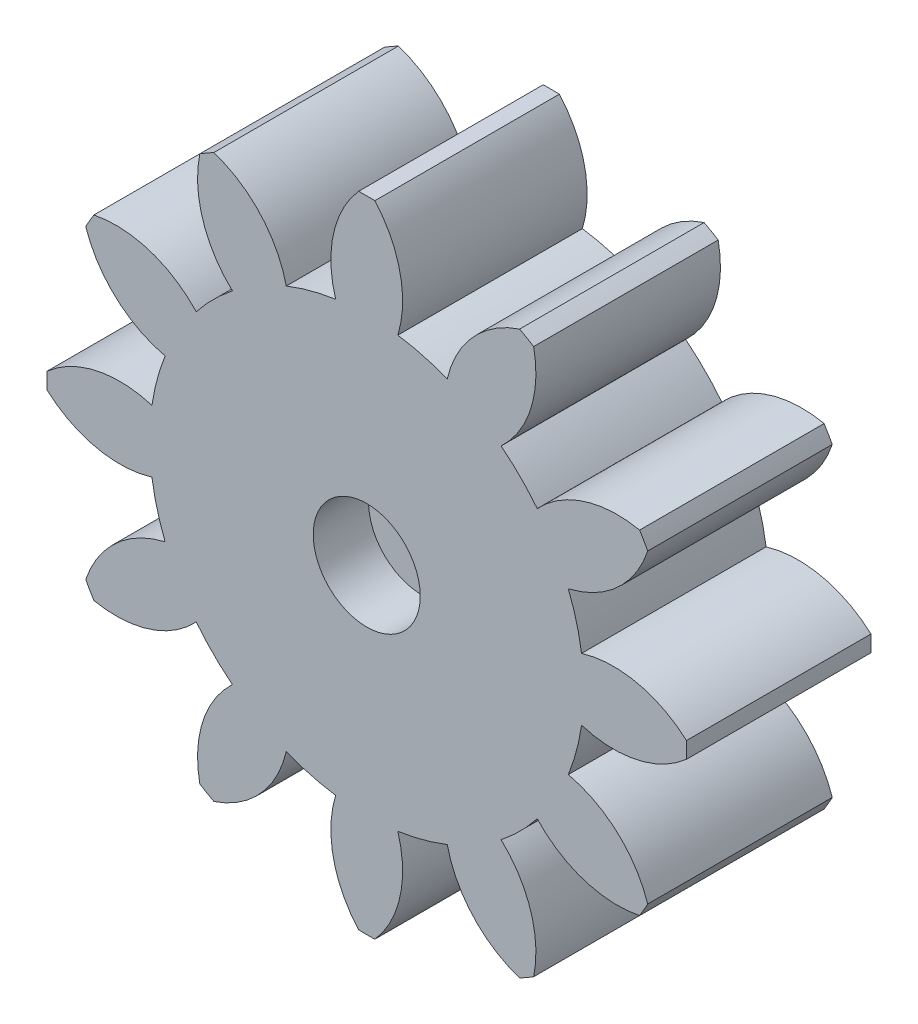
SolidWorks part; units mm, degrees
ref_plane "Front Plane" through (0, 0, 0) normal (0, 0, 1) x (1, 0, 0)
ref_plane "Top Plane" through (0, 0, 0) normal (0, 1, 0) x (1, 0, 0)
ref_plane "Right Plane" through (0, 0, 0) normal (1, 0, 0) x (0, 0, -1)
sketch "Sketch1" plane through (0, 0, 0) normal (0, 0, 1) x (1, 0, 0)
  arc A96 (10.9244, -4.3614) -> (11.6416, -1.6851) centre (0, 0) ccw
  arc A97 (11.6416, -1.6851) -> (17.3299, -0.4402) centre (13.3779, 3.9992) ccw
  arc A98 (17.3299, -0.4402) -> (17.3299, 0.4402) centre (0, 0) ccw
  arc A99 (17.3299, 0.4402) -> (11.6416, 1.6851) centre (13.3779, -3.9992) ccw
  arc A100 (11.6416, 1.6851) -> (10.9244, 4.3614) centre (0, 0) ccw
  arc A101 (10.9244, 4.3614) -> (15.2282, 8.2838) centre (9.586, 10.1524) ccw
  arc A102 (15.2282, 8.2838) -> (14.7881, 9.0462) centre (0, 0) ccw
  arc A103 (14.7881, 9.0462) -> (9.2393, 7.2801) centre (13.5852, 3.2255) ccw
  arc A104 (9.2393, 7.2801) -> (7.2801, 9.2393) centre (0, 0) ccw
  arc A105 (7.2801, 9.2393) -> (9.0462, 14.7881) centre (3.2255, 13.5852) ccw
  arc A106 (9.0462, 14.7881) -> (8.2838, 15.2282) centre (0, 0) ccw
  arc A107 (8.2838, 15.2282) -> (4.3614, 10.9244) centre (10.1524, 9.586) ccw
  arc A108 (4.3614, 10.9244) -> (1.6851, 11.6416) centre (0, 0) ccw
  arc A109 (1.6851, 11.6416) -> (0.4402, 17.3299) centre (-3.9992, 13.3779) ccw
  arc A110 (0.4402, 17.3299) -> (-0.4402, 17.3299) centre (0, 0) ccw
  arc A111 (-0.4402, 17.3299) -> (-1.6851, 11.6416) centre (3.9992, 13.3779) ccw
  arc A112 (-1.6851, 11.6416) -> (-4.3614, 10.9244) centre (0, 0) ccw
  arc A113 (-4.3614, 10.9244) -> (-8.2838, 15.2282) centre (-10.1524, 9.586) ccw
  arc A114 (-8.2838, 15.2282) -> (-9.0462, 14.7881) centre (0, 0) ccw
  arc A115 (-9.0462, 14.7881) -> (-7.2801, 9.2393) centre (-3.2255, 13.5852) ccw
  arc A116 (-7.2801, 9.2393) -> (-9.2393, 7.2801) centre (0, 0) ccw
  arc A117 (-9.2393, 7.2801) -> (-14.7881, 9.0462) centre (-13.5852, 3.2255) ccw
  arc A118 (-14.7881, 9.0462) -> (-15.2282, 8.2838) centre (0, 0) ccw
  arc A119 (-15.2282, 8.2838) -> (-10.9244, 4.3614) centre (-9.586, 10.1524) ccw
  arc A120 (-10.9244, 4.3614) -> (-11.6416, 1.6851) centre (0, 0) ccw
  arc A121 (-11.6416, 1.6851) -> (-17.3299, 0.4402) centre (-13.3779, -3.9992) ccw
  arc A122 (-17.3299, 0.4402) -> (-17.3299, -0.4402) centre (0, 0) ccw
  arc A123 (-17.3299, -0.4402) -> (-11.6416, -1.6851) centre (-13.3779, 3.9992) ccw
  arc A124 (-11.6416, -1.6851) -> (-10.9244, -4.3614) centre (0, 0) ccw
  arc A125 (-10.9244, -4.3614) -> (-15.2282, -8.2838) centre (-9.586, -10.1524) ccw
  arc A126 (-15.2282, -8.2838) -> (-14.7881, -9.0462) centre (0, 0) ccw
  arc A127 (-14.7881, -9.0462) -> (-9.2393, -7.2801) centre (-13.5852, -3.2255) ccw
  arc A128 (-9.2393, -7.2801) -> (-7.2801, -9.2393) centre (0, 0) ccw
  arc A129 (-7.2801, -9.2393) -> (-9.0462, -14.7881) centre (-3.2255, -13.5852) ccw
  arc A130 (-9.0462, -14.7881) -> (-8.2838, -15.2282) centre (0, 0) ccw
  arc A131 (-8.2838, -15.2282) -> (-4.3614, -10.9244) centre (-10.1524, -9.586) ccw
  arc A132 (-4.3614, -10.9244) -> (-1.6851, -11.6416) centre (0, 0) ccw
  arc A133 (-1.6851, -11.6416) -> (-0.4402, -17.3299) centre (3.9992, -13.3779) ccw
  arc A134 (-0.4402, -17.3299) -> (0.4402, -17.3299) centre (0, 0) ccw
  arc A135 (0.4402, -17.3299) -> (1.6851, -11.6416) centre (-3.9992, -13.3779) ccw
  arc A136 (1.6851, -11.6416) -> (4.3614, -10.9244) centre (0, 0) ccw
  arc A137 (4.3614, -10.9244) -> (8.2838, -15.2282) centre (10.1524, -9.586) ccw
  arc A138 (8.2838, -15.2282) -> (9.0462, -14.7881) centre (0, 0) ccw
  arc A139 (9.0462, -14.7881) -> (7.2801, -9.2393) centre (3.2255, -13.5852) ccw
  arc A140 (7.2801, -9.2393) -> (9.2393, -7.2801) centre (0, 0) ccw
  arc A141 (9.2393, -7.2801) -> (14.7881, -9.0462) centre (13.5852, -3.2255) ccw
  arc A142 (14.7881, -9.0462) -> (15.2282, -8.2838) centre (0, 0) ccw
  arc A143 (15.2282, -8.2838) -> (10.9244, -4.3614) centre (9.586, -10.1524) ccw
extrude "Boss-Extrude1" add sketch "Sketch1" along normal blind 10
sketch "Sketch3" plane through (0, 0, 10) normal (0, 0, 1) x (1, 0, 0)
  circle A0 centre (0, 0) radius 2.9
  dimension "D1" = 5.8
extrude "Cut-Extrude1" cut sketch "Sketch3" against normal blind 3
sketch "Sketch4" plane through (0, 0, 0) normal (0, 0, -1) x (-1, 0, 0)
  circle A0 centre (0, 0) radius 2.9 construction
  circle A1 centre (0, 0) radius 2.9
extrude "Cut-Extrude2" cut sketch "Sketch4" against normal offset from surface (5 mm away) 2 up to face at (2.9, 0, 7)
sketch "Sketch5" plane through (0, 0, 5) normal (0, 0, -1) x (-1, 0, 0)
  circle A0 centre (0, 0) radius 1.125
  dimension "D1" = 2.25
extrude "Cut-Extrude3" cut sketch "Sketch5" against normal up to next
sketch "Sketch6" plane through (0, 0, 0) normal (0, 0, -1) x (-1, 0, 0)
  text T0 "<i>Top</i>" font "Century Gothic" height in points 8
extrude "Cut-Extrude4" cut sketch "Sketch6" against normal blind 0.4
